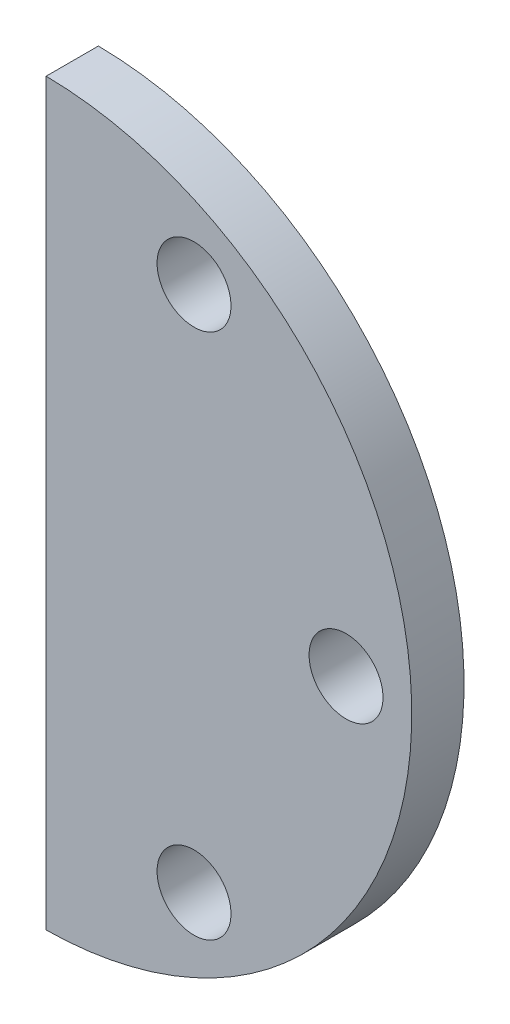
SolidWorks part; units mm, degrees
ref_plane "Front Plane" through (0, 0, 0) normal (0, 0, 1) x (1, 0, 0)
ref_plane "Top Plane" through (0, 0, 0) normal (0, 1, 0) x (1, 0, 0)
ref_plane "Right Plane" through (0, 0, 0) normal (1, 0, 0) x (0, 0, -1)
sketch "Sketch1" plane through (0, 0, 0) normal (0, 0, 1) x (1, 0, 0)
  line L0 (0, 22.5) -> (0, -22.5) construction
  line L1 (0, 0) -> (9.25, 16.0215) construction
  line L2 (0.25, 22.4986) -> (0.25, -22.4986)
  line L3 (-0.25, 22.4986) -> (-0.25, -22.4986)
  line L8 (-12.5, 26) -> (12.5, 26)
  line L9 (-22.5, 16) -> (-22.5, -16)
  line L10 (-12.5, -26) -> (12.5, -26)
  line L11 (22.5, 16) -> (22.5, -16)
  line L12 (13.325, 21.8331) -> (13.325, 18.1669) construction
  line L13 (-16.5, 20) -> (16.5, 20) construction
  line L14 (-16.5, 20) -> (-16.5, -20) construction
  line L15 (-16.5, -20) -> (16.5, -20) construction
  line L16 (16.5, 20) -> (16.5, -20) construction
  line L21 (0.25, 22.4986) -> (0.25, 26)
  line L22 (-0.25, 22.4986) -> (-0.25, 26)
  line L23 (13.325, 18.1669) -> (16.5, 16.3338) construction
  line L24 (16.5, 16.3338) -> (19.675, 18.1669) construction
  line L25 (19.675, 18.1669) -> (19.675, 21.8331) construction
  line L26 (19.675, 21.8331) -> (16.5, 23.6662) construction
  line L27 (16.5, 23.6662) -> (13.325, 21.8331) construction
  line L28 (16.5, 23.6662) -> (16.5, 16.3338) construction
  line L29 (0.25, -22.4986) -> (0.25, -26)
  line L30 (-0.25, -22.4986) -> (-0.25, -26)
  circle A1 centre (9.25, 16.0215) radius 2.25
  circle A5 centre (18.5, 0) radius 2.25
  circle A6 centre (9.25, -16.0215) radius 2.25
  circle A7 centre (-9.25, -16.0215) radius 2.25
  circle A8 centre (-18.5, 0) radius 2.25
  circle A9 centre (0, 0) radius 22.5
  circle A11 centre (-9.25, 16.0215) radius 2.25
  circle A12 centre (16.5, 20) radius 1.4732
  circle A13 centre (-16.5, 20) radius 1.4732
  circle A14 centre (-16.5, -20) radius 1.4732
  circle A15 centre (16.5, -20) radius 1.4732
  arc A16 (-22.5, -16) -> (-12.5, -26) centre (-12.5, -16) ccw
  arc A17 (12.5, -26) -> (22.5, -16) centre (12.5, -16) ccw
  arc A18 (-12.5, 26) -> (-22.5, 16) centre (-12.5, 16) ccw
  arc A19 (12.5, 26) -> (22.5, 16) centre (12.5, 16) cw
  circle A20 centre (16.5, 20) radius 2.3241 construction
  circle A21 centre (16.5, 20) radius 1.0934 construction
  point P22 (0, 0)
  point P25 (0, 0)
  point P28 (0, 26)
  point P29 (-22.5, 0)
  dimension "D3" = 4.5
  dimension "D7" = 18.5
  dimension "D8" = 45
  dimension "D9" = 0.25
  dimension "D6" = 18.5
  dimension "D12" = 2.9464
  dimension "D15" = 10
  dimension "D18" = 4.6482
  dimension "D2" = 18.5
  dimension "D4" = 30
  dimension "D10" = 0.25
  dimension "D11" = 3.5
  dimension "D13" = 6
  dimension "D14" = 6
  dimension "D16" = 6
  dimension "D17" = 6
  dimension "D20" = 6.35
  dimension "D21" = 6.35
  dimension "D5" = 6
extrude "Boss-Extrude1" add sketch "Sketch1" along normal blind 3.18 contours A9 L2 A1 A5 A6
